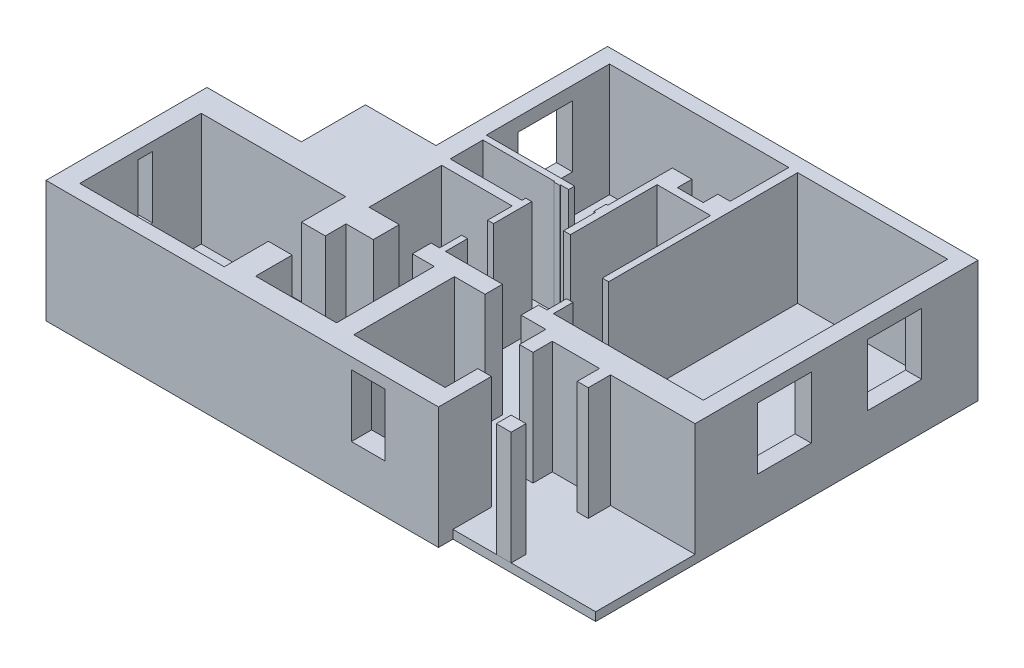
SolidWorks part; units mm, degrees
ref_plane "Спереди" through (0, 0, 0) normal (0, 0, 1) x (1, 0, 0)
ref_plane "Сверху" through (0, 0, 0) normal (0, 1, 0) x (1, 0, 0)
ref_plane "Справа" through (0, 0, 0) normal (1, 0, 0) x (0, 0, -1)
sketch "Эскиз1" plane through (0, 0, 0) normal (0, 1, 0) x (1, 0, 0)
  line L0 (0, 0) -> (4220, 0)
  line L1 (4220, 0) -> (4220, -1380)
  line L2 (4220, -1380) -> (3930, -1380)
  line L3 (3930, -1380) -> (3930, -1722.2944)
  line L4 (3320, -1722.2944) -> (3320, -1380)
  line L5 (3320, -1380) -> (2860, -1380)
  line L6 (2860, -1380) -> (2860, -2900)
  line L7 (2860, -2900) -> (2820, -2900)
  line L8 (0, -2900) -> (0, 0)
  line L9 (2820, -2900) -> (2820, -3185.6444)
  line L10 (2820, -3185.6444) -> (2860, -3185.6444)
  line L11 (2860, -3185.6444) -> (2860, -3940)
  line L12 (2080, -2900) -> (2080, -3040)
  line L13 (2080, -3040) -> (1890, -3040)
  line L14 (1890, -3040) -> (1890, -3060)
  line L15 (2080, -2900) -> (0, -2900)
  line L16 (3020, -3940) -> (3020, -1900.0287)
  line L17 (1890, -3060) -> (1750, -3060)
  line L18 (1750, -3060) -> (1750, -3040)
  line L19 (1750, -3040) -> (60, -3040)
  line L20 (60, -3040) -> (60, -3810)
  line L21 (60, -3810) -> (1750, -3810)
  line L22 (1750, -3810) -> (1750, -3720)
  line L23 (1750, -3720) -> (1890, -3720)
  line L24 (1890, -3720) -> (1890, -4620)
  line L25 (1890, -4620) -> (1750, -4620)
  line L26 (1750, -4620) -> (1750, -4040)
  line L27 (1750, -4040) -> (90, -4040)
  line L28 (90, -4040) -> (90, -5750)
  line L29 (90, -5750) -> (800, -5750)
  line L30 (800, -5750) -> (800, -6360)
  line L31 (800, -6360) -> (723.6696, -6360)
  line L32 (160, -6360) -> (160, -6850)
  line L33 (160, -6850) -> (-400, -6850)
  line L34 (-400, -6850) -> (-400, -5810)
  line L35 (-400, -5810) -> (-3800, -5810)
  line L36 (-3800, -5810) -> (-3800, -8670)
  line L37 (-3800, -8670) -> (-400, -8670)
  line L38 (-400, -8670) -> (-400, -7630)
  line L39 (-400, -7630) -> (160, -7630)
  line L40 (160, -7630) -> (160, -8490)
  line L41 (160, -8490) -> (2065, -8490)
  line L42 (2065, -8490) -> (2065, -6190)
  line L43 (2065, -6190) -> (1550, -6190)
  line L44 (1550, -6190) -> (1550, -5750)
  line L45 (1550, -5750) -> (1750, -5750)
  line L46 (1750, -5750) -> (1750, -5230)
  line L47 (1750, -5230) -> (1890, -5230)
  line L48 (1890, -5230) -> (1890, -5750)
  line L49 (1890, -5750) -> (3230, -5750)
  line L50 (3230, -5750) -> (3230, -6160)
  line L51 (3230, -6160) -> (2510, -6160)
  line L52 (2510, -6160) -> (2510, -8530)
  line L53 (2510, -8530) -> (4660, -8530)
  line L54 (4660, -8530) -> (4660, -7760)
  line L55 (4660, -7760) -> (4980, -7760)
  line L56 (2860, -3940) -> (3020, -3940)
  line L57 (4280, -1900.0287) -> (4280, -4450)
  line L58 (4280, -4450) -> (4430, -4450)
  line L59 (4430, -4450) -> (4430, 0)
  line L60 (4430, 0) -> (7960, 0)
  line L61 (7960, 0) -> (7960, -5750)
  line L62 (7960, -5750) -> (4430, -5750)
  line L63 (4430, -5750) -> (4430, -5290)
  line L64 (4430, -5290) -> (4280, -5290)
  line L65 (-4260, -5215) -> (-4260, -9005)
  line L66 (-2160, -5800.9457) -> (-2160, -8670) construction
  line L67 (4080, -6160) -> (4080, -5750)
  line L68 (4080, -5750) -> (4280, -5750)
  line L69 (4280, -5750) -> (4280, -5290)
  line L70 (4080, -6160) -> (4660, -6160)
  line L71 (4660, -6160) -> (4660, -6780)
  line L72 (4660, -6780) -> (4980, -6780)
  line L73 (723.6696, -6360) -> (160, -6360)
  line L74 (-217.7441, -870) -> (-217.7441, -2150) construction
  line L75 (8168.2501, -990) -> (8168.2501, -2270) construction
  line L76 (8168.2501, -3590) -> (8168.2501, -4860) construction
  line L77 (8249.589, -2900) -> (8168.2501, -2900) construction
  line L78 (8168.2501, -2900) -> (9306.9939, -2900) construction
  line L79 (8340, 335) -> (8340, -6325)
  line L80 (-380, 335) -> (-380, -3705)
  line L81 (2930, -8710.1469) -> (3720, -8710.1469) construction
  line L82 (-380, -3705) -> (-2040, -3705)
  line L83 (-4260, -9005) -> (4980, -9005)
  line L84 (-380, 335) -> (8340, 335)
  line L85 (0, 0) -> (-380, 0) construction
  line L86 (7960, 0) -> (8340, 0) construction
  line L87 (-2040, -3705) -> (-2040, -5215)
  line L88 (-2040, -5215) -> (-4260, -5215)
  line L90 (-400, -8670) -> (-400, -9005) construction
  line L91 (7960, 0) -> (7960, 335) construction
  line L92 (3320, -1722.2944) -> (3930, -1722.2944)
  line L93 (3020, -1900.0287) -> (4280, -1900.0287)
  line L94 (4980, -9005) -> (4980, -7760)
  line L95 (4980, -6325) -> (4980, -6780)
  line L96 (6000, -8315) -> (6000, -8665)
  line L97 (8340, -6325) -> (6350, -6325)
  line L98 (6000, -8665) -> (6350, -8665)
  line L99 (6350, -8665) -> (6350, -8315)
  line L100 (6350, -8315) -> (6000, -8315)
  line L101 (6090, -6325) -> (6090, -6850)
  line L102 (6090, -6850) -> (6350, -6850)
  line L103 (6350, -6850) -> (6350, -6325)
  line L105 (6090, -6325) -> (4980, -6325)
  point P92 (761.8348, -6360)
  point P112 (0, 0)
  dimension "D1" = 4220
  dimension "D2" = 2900
  dimension "D3" = 1380
  dimension "D4" = 1360
  dimension "D5" = 290
  dimension "D6" = 900
  dimension "D7" = 40
  dimension "D8" = 780
  dimension "D9" = 970
  dimension "D10" = 1130
  dimension "D11" = 140
  dimension "D12" = 770
  dimension "D13" = 1690
  dimension "D14" = 1830
  dimension "D15" = 20
  dimension "D16" = 680
  dimension "D17" = 410
  dimension "D18" = 2190
  dimension "D19" = 580
  dimension "D20" = 1800
  dimension "D21" = 1710
  dimension "D22" = 710
  dimension "D23" = 1460
  dimension "D24" = 2390
  dimension "D25" = 2190
  dimension "D26" = 1340
  dimension "D27" = 460
  dimension "D28" = 1300
  dimension "D29" = 3940
  dimension "D30" = 5750
  dimension "D31" = 620
  dimension "D32" = 1600
  dimension "D33" = 380
  dimension "D34" = 350
  dimension "D35" = 2150
  dimension "D36" = 2370
  dimension "D37" = 150
  dimension "D38" = 1990
  dimension "D39" = 1040
  dimension "D40" = 8720
  dimension "D41" = 6070
  dimension "D42" = 870
  dimension "D43" = 2150
  dimension "D44" = 890
  dimension "D45" = 2160
  dimension "D46" = 3480
  dimension "D47" = 4760
  dimension "D48" = 2850
  dimension "D49" = 9340
  dimension "D50" = 1660
  dimension "D51" = 2130
  dimension "D52" = 2740
  dimension "D53" = 490
  dimension "D54" = 1270
  dimension "D55" = 3960
  dimension "D56" = 640
  dimension "D57" = 1265
  dimension "D58" = 440
  dimension "D59" = 3400
  dimension "D60" = 1040
  dimension "D61" = 1760
  dimension "D62" = 940
  dimension "D63" = 1730
  dimension "D64" = 1510
  dimension "D65" = 335
  dimension "D66" = 4040
  dimension "D67" = 3360
  dimension "D68" = 2680
  dimension "D69" = 260
  dimension "D70" = 525
  dimension "D71" = 340
  dimension "D72" = 9240
extrude "Бобышка-Вытянуть1" add sketch "Эскиз1" along normal blind 2665
sketch "Эскиз2" plane through (0, 0, 0) normal (0, -1, 0) x (1, 0, 0)
  line L0 (-4260, 5215) -> (-4260, 9005) construction
  line L1 (-2040, 5215) -> (-4260, 5215) construction
  line L2 (-2040, 3705) -> (-2040, 5215) construction
  line L3 (-380, 3705) -> (-2040, 3705) construction
  line L4 (-380, -335) -> (-380, 3705) construction
  line L5 (8340, -335) -> (-380, -335) construction
  line L7 (-4260, 9005) -> (4980, 9005) construction
  line L8 (-4260, 5215) -> (-4260, 9005)
  line L9 (-2040, 5215) -> (-4260, 5215)
  line L10 (-2040, 3705) -> (-2040, 5215)
  line L11 (-380, 3705) -> (-2040, 3705)
  line L12 (-380, -335) -> (-380, 3705)
  line L13 (8340, -335) -> (-380, -335)
  line L15 (-4260, 9005) -> (4980, 9005)
  line L16 (8340, 6325) -> (8340, -335) construction
  line L17 (8340, 8665) -> (8340, -335)
  line L18 (6000, 8665) -> (6350, 8665) construction
  line L19 (4980, 8665) -> (8340, 8665)
  line L20 (4980, 9005) -> (4980, 7760) construction
  line L21 (4980, 9005) -> (4980, 8665)
  point P7 (8340, 8665)
  point P9 (0, 0)
  point P10 (8340, 9005)
  point P12 (8258.9078, 9005)
  point P15 (4945, 8665)
  point P18 (5012.5927, 8665)
extrude "Бобышка-Вытянуть2" add sketch "Эскиз2" along normal blind 200
sketch "Эскиз3" plane through (8340, 0, 0) normal (1, 0, 0) x (0, 0, -1)
  line L0 (-5750, 2665) -> (-5750, 0) construction
  line L1 (-4860, 900) -> (-3590, 900)
  line L2 (-4860, 900) -> (-4860, 2350)
  line L3 (-4860, 2350) -> (-3590, 2350)
  line L4 (-3590, 900) -> (-3590, 2350)
  line L5 (-2270, 900) -> (-990, 900)
  line L6 (-2270, 900) -> (-2270, 2350)
  line L7 (-2270, 2350) -> (-990, 2350)
  line L8 (-990, 900) -> (-990, 2350)
  line L9 (0, 0) -> (-4450, 0) construction
  dimension "D1" = 890
  dimension "D2" = 2160
  dimension "D3" = 3480
  dimension "D4" = 4760
  dimension "D5" = 900
  dimension "D6" = 1450
extrude "Вырез-Вытянуть1" cut sketch "Эскиз3" against normal up to surface (380 mm away) up to face at (7960, 1332.5, 2875)
sketch "Эскиз4" plane through (-380, 0, 0) normal (-1, 0, 0) x (0, 0, 1)
  line L0 (1380, 0) -> (0, 0) construction
  line L1 (870, 2350) -> (2150, 2350)
  line L2 (870, 2350) -> (870, 900)
  line L3 (870, 900) -> (2150, 900)
  line L4 (2150, 2350) -> (2150, 900)
  line L5 (0, 2665) -> (0, 0) construction
  dimension "D1" = 900
  dimension "D2" = 1450
  dimension "D3" = 870
  dimension "D4" = 2150
extrude "Вырез-Вытянуть2" cut sketch "Эскиз4" against normal up to next (380 mm away)
sketch "Эскиз5" plane through (-4260, 0, 0) normal (-1, 0, 0) x (0, 0, 1)
  line L0 (8670, 0) -> (7630, 0) construction
  line L1 (6954.3167, 1000) -> (7300.9323, 1000)
  line L2 (6954.3167, 1000) -> (6954.3167, 2460)
  line L3 (6954.3167, 2460) -> (7300.9323, 2460)
  line L4 (7300.9323, 1000) -> (7300.9323, 2460)
  dimension "D1" = 1000
  dimension "D2" = 1460
extrude "Вырез-Вытянуть3" cut sketch "Эскиз5" against normal up to next (460 mm away)
sketch "Эскиз6" plane through (0, 0, 9005) normal (0, 0, 1) x (1, 0, 0)
  line L0 (4660, 2665) -> (4660, 0) construction
  line L1 (2930, 935) -> (3720, 935)
  line L2 (2930, 935) -> (2930, 2400)
  line L3 (2930, 2400) -> (3720, 2400)
  line L4 (3720, 935) -> (3720, 2400)
  line L5 (4660, 0) -> (4080, 0) construction
  dimension "D1" = 940
  dimension "D2" = 1730
  dimension "D3" = 935
  dimension "D4" = 1465
extrude "Вырез-Вытянуть4" cut sketch "Эскиз6" against normal up to next (475 mm away)
